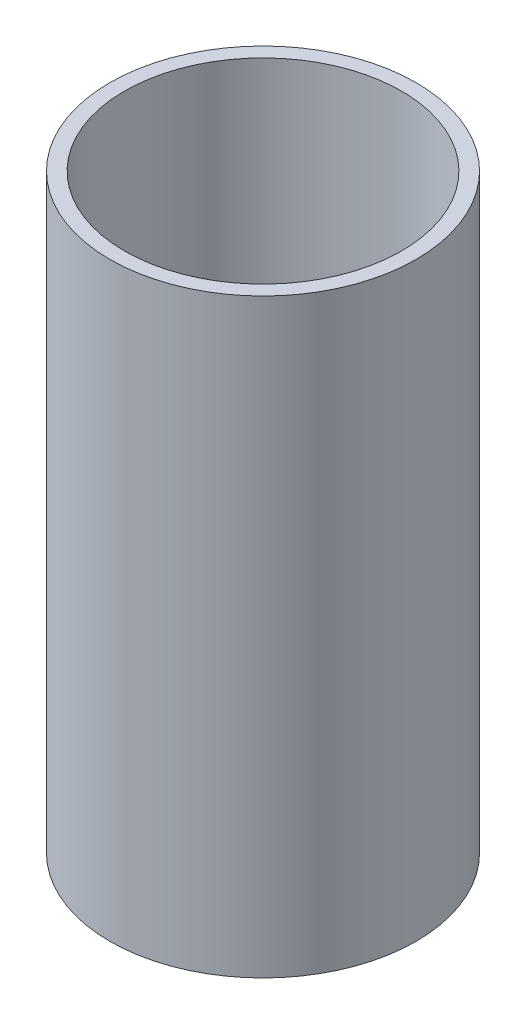
SolidWorks part; units mm, degrees
ref_plane "Front Plane" through (0, 0, 0) normal (0, 0, 1) x (1, 0, 0)
ref_plane "Top Plane" through (0, 0, 0) normal (0, 1, 0) x (1, 0, 0)
ref_plane "Right Plane" through (0, 0, 0) normal (1, 0, 0) x (0, 0, -1)
sketch "Sketch1" plane through (0, 0, 0) normal (0, 1, 0) x (1, 0, 0)
  circle A0 centre (0, 0) radius 10.5
extrude "Boss-Extrude1" add sketch "Sketch1" along normal blind 40.5
shell "Shell1" thickness 1
